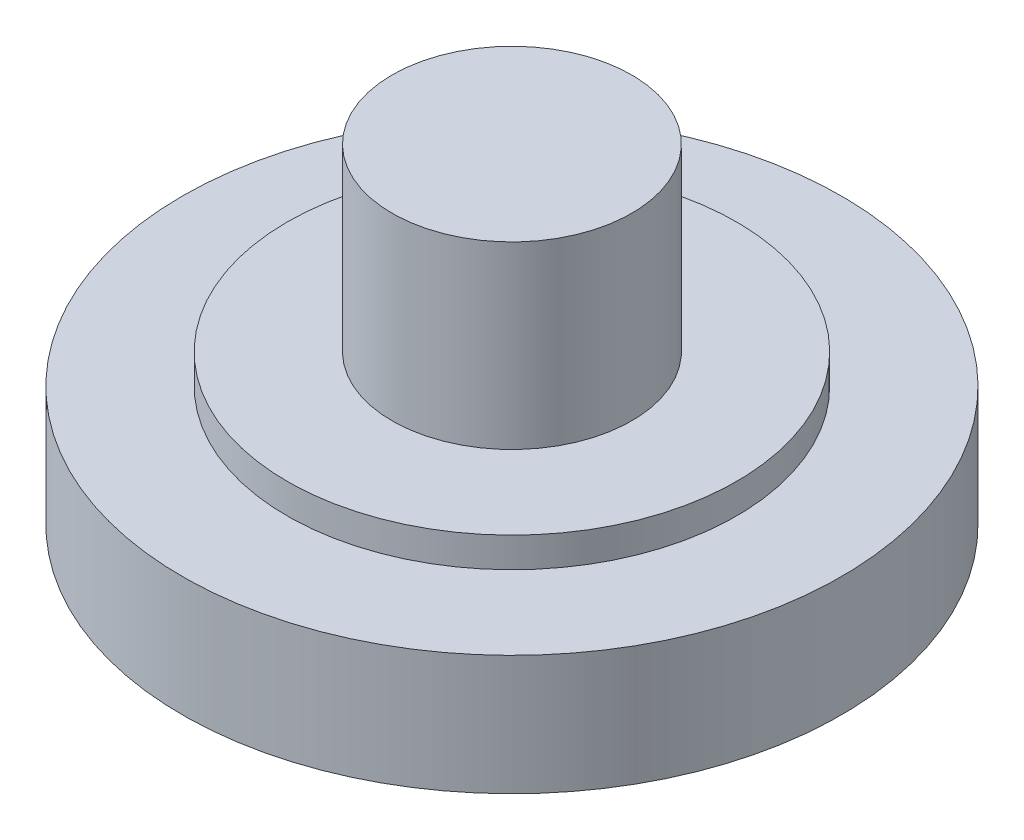
SolidWorks part; units mm, degrees
ref_plane "Front Plane" through (0, 0, 0) normal (0, 0, 1) x (1, 0, 0)
ref_plane "Top Plane" through (0, 0, 0) normal (0, 1, 0) x (1, 0, 0)
ref_plane "Right Plane" through (0, 0, 0) normal (1, 0, 0) x (0, 0, -1)
sketch "Sketch1" plane through (0, 0, 0) normal (0, 0, 1) x (1, 0, 0)
  line L0 (0, 0) -> (5.5, 0)
  line L1 (5.5, 0) -> (5.5, 2)
  line L2 (5.5, 2) -> (3.75, 2)
  line L3 (3.75, 2) -> (3.75, 2.5)
  line L4 (3.75, 2.5) -> (2, 2.5)
  line L5 (2, 2.5) -> (2, 5.5)
  line L6 (2, 5.5) -> (0, 5.5)
  line L7 (0, 5.5) -> (0, 0) construction
  line L8 (0, 0) -> (0, 5.5)
  dimension "D1" = 5.5
  dimension "D2" = 2
  dimension "D3" = 0.5
  dimension "D4" = 3
  dimension "D5" = 2
revolve "Revolve1" add sketch "Sketch1" angle 360 about L7
